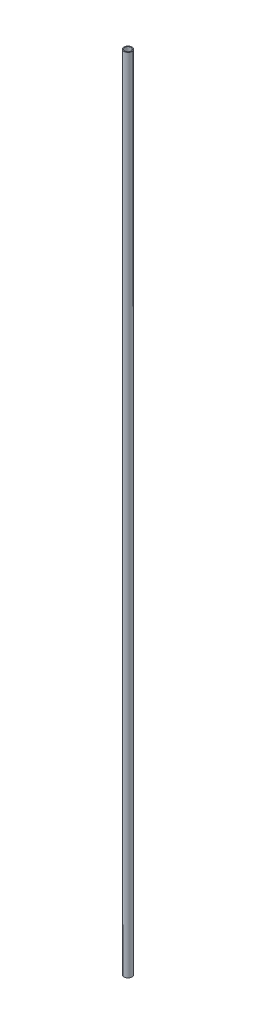
SolidWorks part; units mm, degrees
material "Thornel Mat VMA"
ref_plane "Alzado" through (0, 0, 0) normal (0, 0, 1) x (1, 0, 0)
ref_plane "Planta" through (0, 0, 0) normal (0, 1, 0) x (1, 0, 0)
ref_plane "Vista lateral" through (0, 0, 0) normal (1, 0, 0) x (0, 0, -1)
sketch "Croquis1" plane through (0, 0, 0) normal (0, 1, 0) x (1, 0, 0)
  circle A0 centre (0, 0) radius 5
  circle A1 centre (0, 0) radius 4
  dimension "D1" = 10
  dimension "D2" = 8
extrude "Saliente-Extruir1" add sketch "Croquis1" along normal blind 1020
